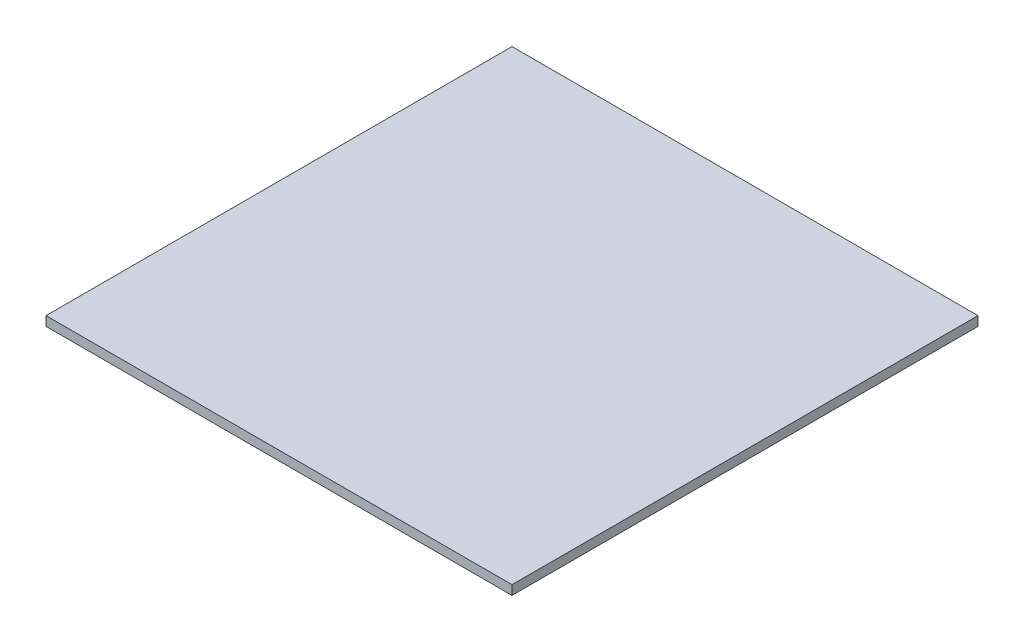
SolidWorks part; units mm, degrees
ref_plane "Alzado" through (0, 0, 0) normal (0, 0, 1) x (1, 0, 0)
ref_plane "Planta" through (0, 0, 0) normal (0, 1, 0) x (1, 0, 0)
ref_plane "Vista lateral" through (0, 0, 0) normal (1, 0, 0) x (0, 0, -1)
sketch "Croquis1" plane through (0, 0, 0) normal (0, 1, 0) x (1, 0, 0)
  line L1 (-250, -250) -> (250, -250)
  line L2 (-250, -250) -> (-250, 250)
  line L3 (-250, 250) -> (250, 250)
  line L4 (250, -250) -> (250, 250)
  line L5 (-250, -250) -> (250, 250) construction
  line L6 (-250, 250) -> (250, -250) construction
  point P0 (0, 0)
  dimension "D1" = 500
  dimension "D2" = 500
extrude "Saliente-Extruir1" add sketch "Croquis1" along normal blind 10
